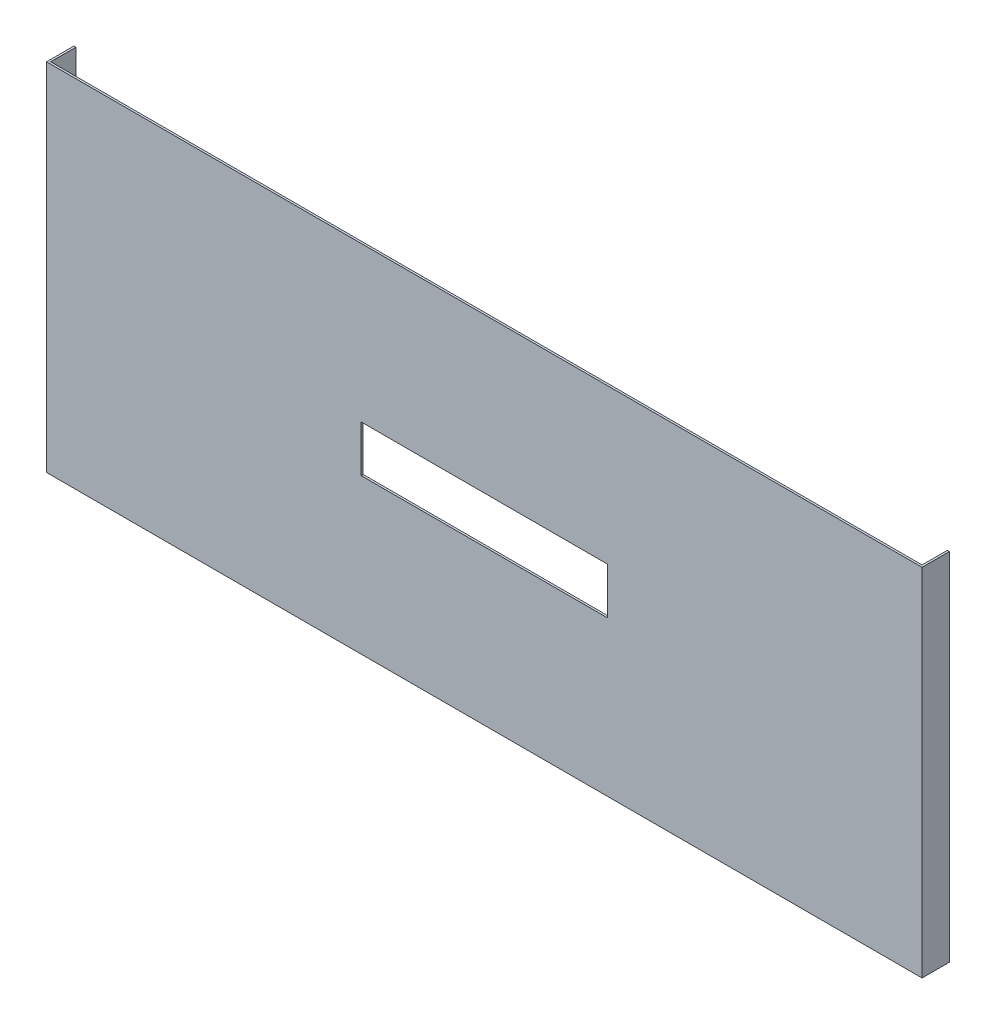
SolidWorks part; units mm, degrees
ref_plane "Front Plane" through (0, 0, 0) normal (0, 0, 1) x (1, 0, 0)
ref_plane "Top Plane" through (0, 0, 0) normal (0, 1, 0) x (1, 0, 0)
ref_plane "Right Plane" through (0, 0, 0) normal (1, 0, 0) x (0, 0, -1)
other "Configuration Table"
sketch "Sketch1" plane through (0, 0, 0) normal (0, 1, 0) x (1, 0, 0)
  line L0 (30, -40) -> (30, -20)
  line L1 (30, -20) -> (31.5, -20)
  line L2 (31.5, -20) -> (31.5, -38.5)
  line L3 (31.5, -38.5) -> (668.5, -38.5)
  line L4 (668.5, -38.5) -> (668.5, -20)
  line L5 (668.5, -20) -> (670, -20)
  line L6 (670, -20) -> (670, -40)
  line L7 (670, -40) -> (30, -40)
extrude "TOPPING_klape_alt2_kapak_1" add sketch "Sketch1" along normal blind 260 from offset 200 separate body
sketch "Sketch2" plane through (0, 0, 0) normal (0, 0, 1) x (1, 0, 0)
  line L1 (260, 313) -> (440, 313)
  line L2 (260, 313) -> (260, 347)
  line L3 (260, 347) -> (440, 347)
  line L4 (440, 313) -> (440, 347)
extrude "TOPPING_klape_alt2_kapak_2" cut sketch "Sketch2" along normal blind 14 from offset 27
